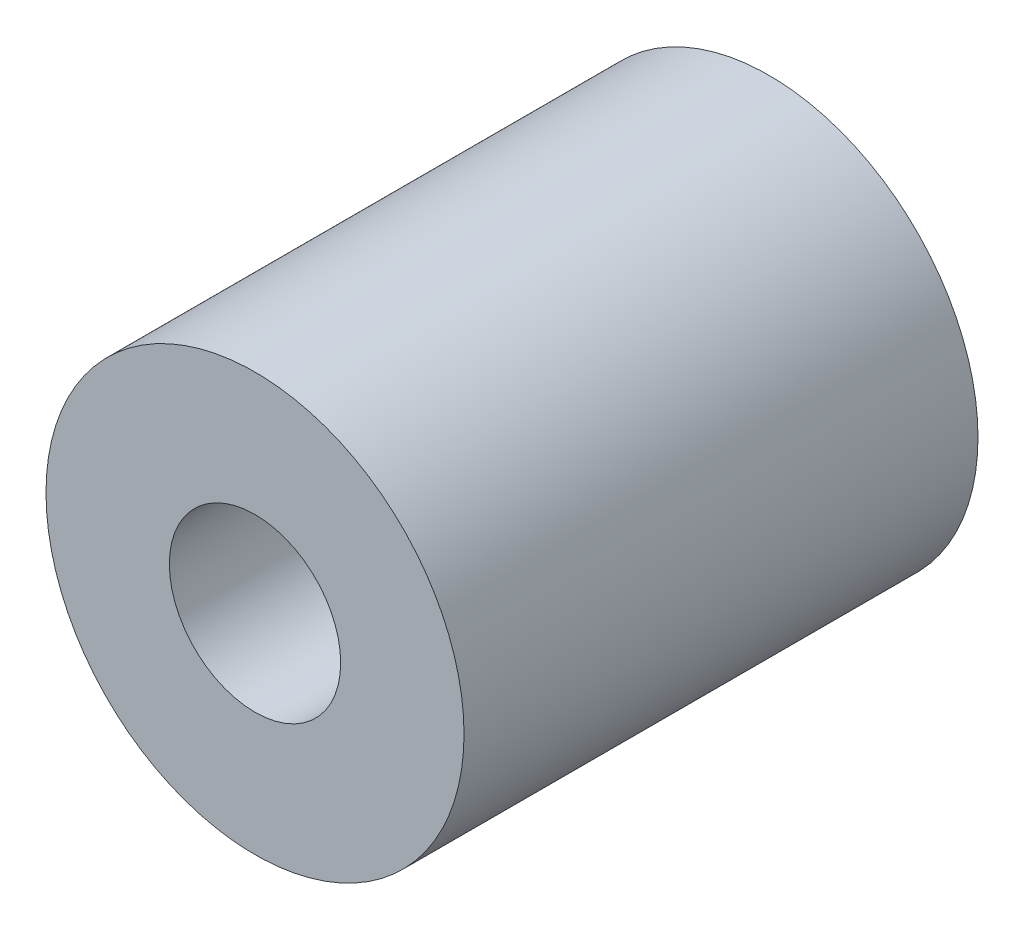
SolidWorks part; units mm, degrees
material "Brass"
ref_plane "Front Plane" through (0, 0, 0) normal (0, 0, 1) x (1, 0, 0)
ref_plane "Top Plane" through (0, 0, 0) normal (0, 1, 0) x (1, 0, 0)
ref_plane "Right Plane" through (0, 0, 0) normal (1, 0, 0) x (0, 0, -1)
sketch "Sketch1" plane through (0, 0, 0) normal (0, 0, 1) x (1, 0, 0)
  circle A0 centre (0, 0) radius 30.988
extrude "Boss-Extrude1" add sketch "Sketch1" along normal mid plane 76.2
sketch "Sketch2" plane through (0, 0, 38.1) normal (0, 0, 1) x (1, 0, 0)
  circle A0 centre (0, 0) radius 12.7
extrude "Cut-Extrude1" cut sketch "Sketch2" against normal blind 25.4
